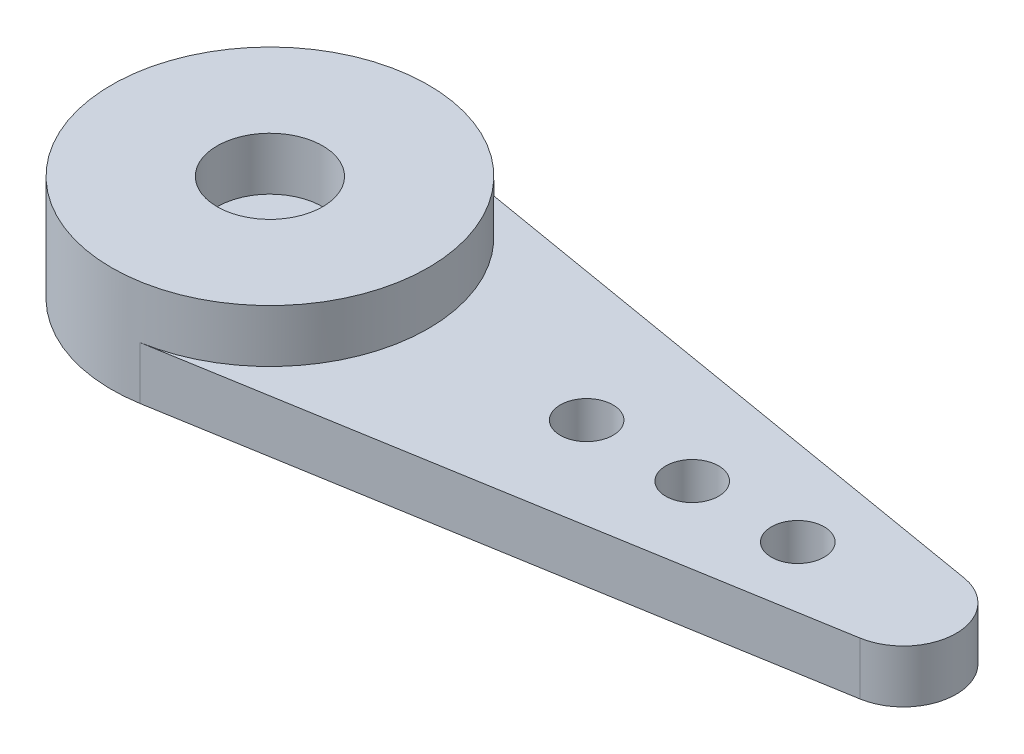
SolidWorks part; units mm, degrees
ref_plane "Front Plane" through (0, 0, 0) normal (0, 0, 1) x (1, 0, 0)
ref_plane "Top Plane" through (0, 0, 0) normal (0, 1, 0) x (1, 0, 0)
ref_plane "Right Plane" through (0, 0, 0) normal (1, 0, 0) x (0, 0, -1)
sketch "Sketch1" plane through (0, 0, 0) normal (0, 1, 0) x (1, 0, 0)
  line L0 (1.8167, 0) -> (60, 0) construction
  line L1 (2.5, 14.7902) -> (60.8333, 4.9301)
  line L2 (2.5, -14.7902) -> (60.8333, -4.9301)
  arc A0 (2.5, 14.7902) -> (2.5, -14.7902) centre (0, 0) ccw
  arc A1 (60.8333, -4.9301) -> (60.8333, 4.9301) centre (60, 0) ccw
  dimension "D1" = 30
  dimension "D2" = 10
  dimension "D3" = 60
extrude "Boss-Extrude1" add sketch "Sketch1" along normal blind 5
sketch "Sketch2" plane through (0, 5, 0) normal (0, 1, 0) x (1, 0, 0)
  circle A0 centre (0, 0) radius 15
  dimension "D1" = 30
extrude "Boss-Extrude2" add sketch "Sketch2" along normal blind 5
sketch "Sketch3" plane through (0, 10, 0) normal (0, 1, 0) x (1, 0, 0)
  circle A0 centre (0, 0) radius 5
  dimension "D1" = 10
extrude "Cut-Extrude1" cut sketch "Sketch3" against normal blind 5
sketch "Sketch4" plane through (0, 5, 0) normal (0, 1, 0) x (1, 0, 0)
  circle A0 centre (50, 0) radius 2.5
  circle A1 centre (40, 0) radius 2.5
  circle A2 centre (30, 0) radius 2.5
  dimension "D1" = 5
  dimension "D2" = 50
  dimension "D3" = 3
extrude "Cut-Extrude2" cut sketch "Sketch4" against normal blind 5
scale "Scale1" scale about centroid uniform scaling yes scale factor 0.6
